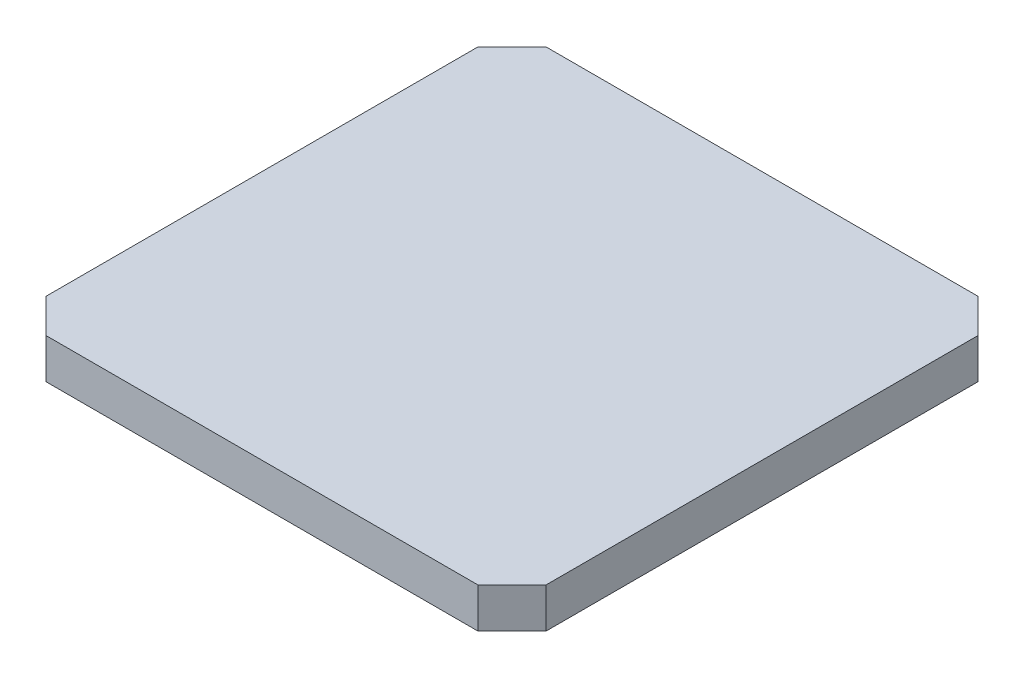
SolidWorks part; units mm, degrees
material "GPS"
ref_plane "Front Plane" through (0, 0, 0) normal (0, 0, 1) x (1, 0, 0)
ref_plane "Top Plane" through (0, 0, 0) normal (0, 1, 0) x (1, 0, 0)
ref_plane "Right Plane" through (0, 0, 0) normal (1, 0, 0) x (0, 0, -1)
sketch "Sketch1" plane through (0, 0, 0) normal (0, 1, 0) x (1, 0, 0)
  line L0 (0, 1.7) -> (1.7, 0)
  line L1 (1.7, 0) -> (23.3, 0)
  line L2 (0, 1.7) -> (0, 23.3)
  line L3 (1.7, 25) -> (23.3, 25)
  line L4 (25, 1.7) -> (25, 23.3)
  line L5 (23.3, 0) -> (25, 1.7)
  line L6 (23.3, 25) -> (25, 23.3)
  line L7 (0, 23.3) -> (1.7, 25)
  point P0 (0, 0)
  point P1 (25, 25)
  point P2 (0, 25)
  point P3 (25, 0)
  dimension "D1" = 25
  dimension "D2" = 25
extrude "GPS Antenna" add sketch "Sketch1" along normal blind 2
sketch "Sketch2" plane through (0, 0, 0) normal (0, 1, 0) x (1, 0, 0)
  line L1 (0, 0) -> (20, 0)
  line L2 (0, 0) -> (0, 20)
  line L3 (0, 20) -> (20, 20)
  line L4 (20, 0) -> (20, 20)
  dimension "D1" = 20
  dimension "D2" = 20
extrude "Boss-Extrude2" [suppressed] add sketch "Sketch2" along normal blind 2.54
